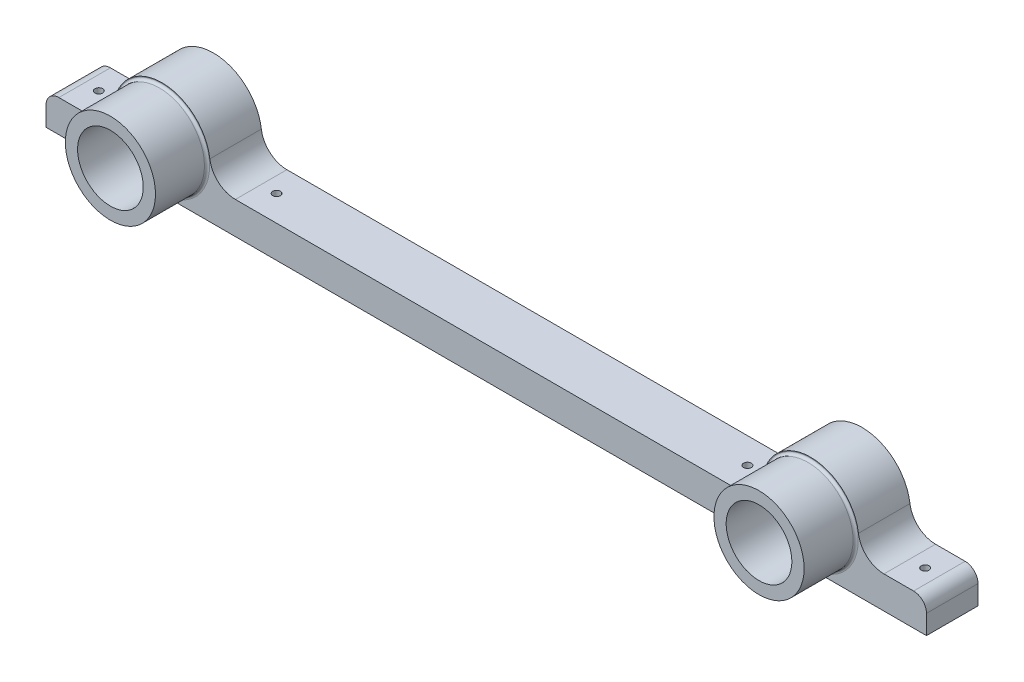
SolidWorks part; units mm, degrees
ref_plane "Front Plane" through (0, 0, 0) normal (0, 0, 1) x (1, 0, 0)
ref_plane "Top Plane" through (0, 0, 0) normal (0, 1, 0) x (1, 0, 0)
ref_plane "Right Plane" through (0, 0, 0) normal (1, 0, 0) x (0, 0, -1)
sketch "Sketch1" plane through (0, 0, 0) normal (0, 0, 1) x (1, 0, 0)
  line L0 (6.35, 4.7625) -> (70.2996, 4.7625) construction
  line L1 (0, 0) -> (76.6496, 0)
  line L2 (0, 9.525) -> (0, 0) construction
  line L3 (0, 9.525) -> (76.6496, 9.525) construction
  line L4 (76.6496, 9.525) -> (76.6496, 0) construction
  line L5 (0, 9.525) -> (0, 3.175) construction
  line L6 (0, 3.175) -> (-5.08, 3.175)
  line L7 (-5.08, 3.175) -> (-5.08, 0)
  line L8 (-5.08, 0) -> (0, 0)
  line L9 (76.6496, 9.525) -> (76.6496, 3.175) construction
  line L10 (76.6496, 3.175) -> (81.7296, 3.175)
  line L11 (81.7296, 3.175) -> (81.7296, 0)
  line L12 (81.7296, 0) -> (76.6496, 0)
  line L13 (0, 3.175) -> (1.5875, 3.175)
  line L14 (6.35, 9.525) -> (6.35, 0) construction
  line L15 (1.5875, 3.175) -> (1.5875, 4.7625)
  line L16 (75.0621, 4.7625) -> (75.0621, 3.175)
  line L17 (75.0621, 3.175) -> (76.6496, 3.175)
  line L18 (70.2996, 4.7625) -> (75.0621, 4.7625) construction
  line L19 (70.2996, 9.525) -> (70.2996, 4.7625) construction
  line L20 (11.1125, 4.7625) -> (11.1125, 3.175)
  line L21 (11.1125, 3.175) -> (65.5371, 3.175)
  line L22 (65.5371, 3.175) -> (65.5371, 4.7625)
  line L23 (6.35, 4.7625) -> (1.5875, 4.7625) construction
  circle A0 centre (6.35, 4.7625) radius 3.175 construction
  circle A1 centre (70.2996, 4.7625) radius 3.175 construction
  circle A2 centre (6.35, 4.7625) radius 0.635
  circle A3 centre (70.2996, 4.7625) radius 0.635
  circle A4 centre (6.35, 4.7625) radius 4.7625 construction
  circle A5 centre (70.2996, 4.7625) radius 4.7625 construction
  arc A6 (1.5875, 4.7625) -> (11.1125, 4.7625) centre (6.35, 4.7625) cw
  arc A7 (75.0621, 4.7625) -> (65.5371, 4.7625) centre (70.2996, 4.7625) ccw
  point P18 (38.3248, 4.7625)
  dimension "D1" = 6.35
  dimension "D2" = 6.35
  dimension "D11" = 1.27
  dimension "D3" = 5.08
  dimension "D4" = 3.175
  dimension "D5" = 3.175
  dimension "D6" = 5.08
  dimension "D7" = 6.35
  dimension "D8" = 63.9496
  dimension "D9" = 6.35
  dimension "D10" = 6.35
extrude "Boss-Extrude1" add sketch "Sketch1" along normal blind 5.08
sketch "Sketch2" plane through (0, 0, 5.08) normal (0, 0, 1) x (1, 0, 0)
  circle A0 centre (6.35, 4.7625) radius 4.445
  circle A1 centre (70.2996, 4.7625) radius 4.445
  circle A2 centre (6.35, 4.7625) radius 0.635 construction
  circle A3 centre (70.2996, 4.7625) radius 0.635 construction
  circle A4 centre (6.35, 4.7625) radius 0.635
  circle A5 centre (70.2996, 4.7625) radius 0.635
  dimension "D1" = 8.89
  dimension "D2" = 8.89
extrude "Boss-Extrude2" add sketch "Sketch2" along normal blind 5.08
sketch "Sketch3" plane through (0, 0, 10.16) normal (0, 0, 1) x (1, 0, 0)
  circle A0 centre (6.35, 4.7625) radius 3.2385
  circle A1 centre (70.2996, 4.7625) radius 3.2385
  dimension "D1" = 6.477
  dimension "D2" = 6.477
extrude "Cut-Extrude1" cut sketch "Sketch3" against normal blind 6.35
fillet "Fillet1" radius 0.254 2 edges at (74.7446, 4.7625, 5.08) (10.795, 4.7625, 5.08)
fillet "Fillet2" radius 2.54 4 edges at (75.0621, 3.175, 2.54) (11.1125, 3.175, 2.54) (65.5371, 3.175, 2.54) (1.5875, 3.175, 2.54)
fillet "Fillet3" radius 1.27 2 edges at (81.7296, 3.175, 2.54) (-5.08, 3.175, 2.54)
sketch "Sketch5" plane through (0, 3.175, 0) normal (0, 1, 0) x (1, 0, 0)
  line L0 (15.113, -2.54) -> (38.3248, -2.54) construction
  line L1 (6.35, -10.16) -> (6.35, 0) construction
  line L2 (1.905, -10.16) -> (10.795, -10.16) construction
  line L3 (-5.08, -2.54) -> (81.7296, -2.54) construction
  line L4 (-5.08, -5.08) -> (-5.08, 0) construction
  line L5 (81.7296, 0) -> (81.7296, -5.08) construction
  line L6 (38.3248, -2.54) -> (61.5366, -2.54) construction
  line L7 (11.0718, 0) -> (1.6282, 0) construction
  line L8 (70.2996, -10.16) -> (70.2996, 0) construction
  line L9 (65.8546, -10.16) -> (74.7446, -10.16) construction
  line L10 (75.0214, 0) -> (65.5778, 0) construction
  circle A0 centre (-2.413, -2.54) radius 0.381
  circle A2 centre (79.0626, -2.54) radius 0.381
  circle A3 centre (61.5366, -2.54) radius 0.381
  circle A4 centre (15.113, -2.54) radius 0.381
  dimension "D1" = 0.762
  dimension "D2" = 2.667
  dimension "D3" = 8.763
  dimension "D4" = 8.763
  dimension "D5" = 8.763
  dimension "D6" = 8.763
extrude "Cut-Extrude3" cut sketch "Sketch5" against normal through all
equation "\"D2@Sketch2\"=\"D1@Sketch2\""
equation "\"D3@Sketch5\"=\"D5@Sketch5\""
equation "\"D4@Sketch5\"=\"D5@Sketch5\""
equation "\"D6@Sketch5\"=\"D5@Sketch5\""
